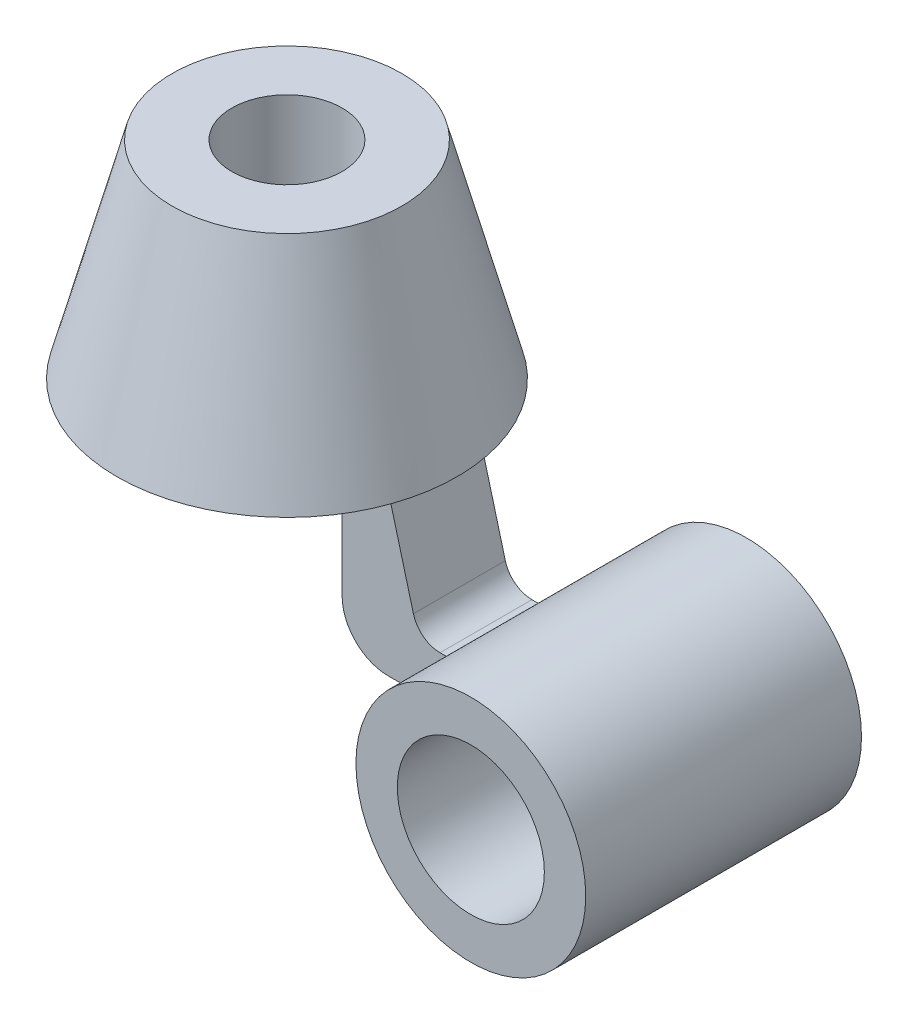
SolidWorks part; units mm, degrees
ref_plane "Front Plane" through (0, 0, 0) normal (0, 0, 1) x (1, 0, 0)
ref_plane "Top Plane" through (0, 0, 0) normal (0, 1, 0) x (1, 0, 0)
ref_plane "Right Plane" through (0, 0, 0) normal (1, 0, 0) x (0, 0, -1)
sketch "Sketch1" plane through (0, 0, 0) normal (0, 0, 1) x (1, 0, 0)
  line L0 (0, 0) -> (37, 0)
  line L1 (37, 0) -> (25, 45)
  line L2 (25, 45) -> (0, 45)
  line L4 (0, 45) -> (0, 0)
  point P3 (74, 0)
  point P6 (38.9098, 45)
  dimension "D1" = 45
  dimension "D2" = 37
  dimension "D3" = 25
revolve "Revolve1" add sketch "Sketch1" angle 360 about L4
sketch "Sketch2" plane through (0, 0, 0) normal (0, 0, 1) x (1, 0, 0)
  line L0 (-37, 0) -> (37, 0) construction
  circle A0 centre (70, -35) radius 25
  dimension "D3" = 50
  dimension "D1" = 35
  dimension "D2" = 70
extrude "Boss-Extrude1" add sketch "Sketch2" along normal mid plane 60 separate body
sketch "Sketch3" plane through (0, 0, 0) normal (0, 0, 1) x (1, 0, 0)
  line L0 (22, 0) -> (22, -35)
  line L1 (-37, 0) -> (37, 0) construction
  line L2 (22, -35) -> (54.1887, -35)
  line L3 (54.1887, -35) -> (54.1887, -25)
  line L4 (54.1887, -25) -> (38.6987, -25)
  line L5 (38.6987, -25) -> (32, 0)
  line L6 (32, 0) -> (22, 0)
  dimension "D2" = 10
  dimension "D3" = 15
  dimension "D4" = 10
  dimension "D5" = 22
extrude "Boss-Extrude2" add sketch "Sketch3" along normal mid plane 20
fillet "Fillet1" radius 10 1 edges at (22, -35, 0)
fillet "Fillet2" radius 6 1 edges at (38.6987, -25, 0)
hole_wizard "Ø1.0mm Dowel Hole1" positions "Sketch4" profile "Sketch5" hole size "Ø1.0" standard "ISO" end condition through all
sketch "Sketch4" plane through (0, 45, 0) normal (0, 1, 0) x (1, 0, 0)
  point P0 (0, 0)
sketch "Sketch5" plane through (0, 45, 0) normal (1, 0, 0) x (0, 0, 1)
  line L0 (0, 0) -> (0, 105)
  line L1 (0, 105) -> (12, 105)
  line L2 (12, 105) -> (12, 0)
  line L5 (12, 0) -> (0, 0)
  line L11 (0, -6.35) -> (0, 107.95) construction
  dimension "Thru Hole Dia." = 24
  dimension "Thru Hole Depth" = 105
hole_wizard "Ø1.0mm Dowel Hole2" positions "Sketch6" profile "Sketch7" hole size "Ø1.0" standard "ISO" end condition through all
sketch "Sketch6" plane through (0, 0, 30) normal (0, 0, 1) x (1, 0, 0)
  point P0 (70, -35)
sketch "Sketch7" plane through (70, -35, 30) normal (1, 0, 0) x (0, -1, 0)
  line L0 (0, 0) -> (0, 67)
  line L1 (0, 67) -> (16, 67)
  line L2 (16, 67) -> (16, 0)
  line L5 (16, 0) -> (0, 0)
  line L11 (0, -6.35) -> (0, 107.95) construction
  dimension "Thru Hole Dia." = 32
  dimension "Thru Hole Depth" = 67
